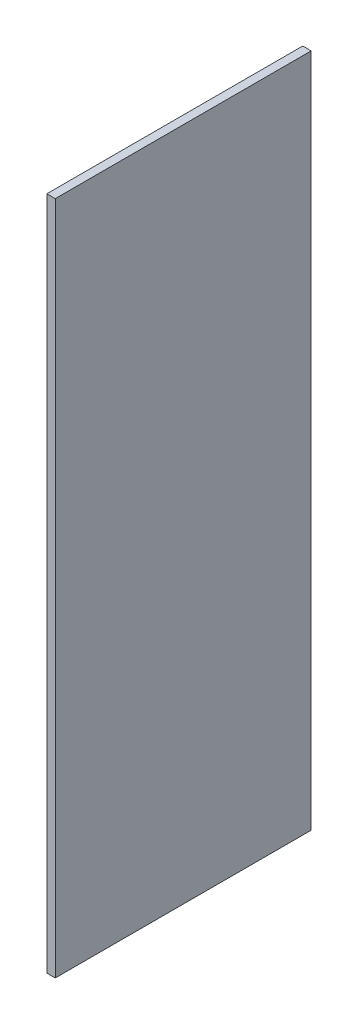
SolidWorks part; units mm, degrees
ref_plane "Front Plane" through (0, 0, 0) normal (0, 0, 1) x (1, 0, 0)
ref_plane "Top Plane" through (0, 0, 0) normal (0, 1, 0) x (1, 0, 0)
ref_plane "Right Plane" through (0, 0, 0) normal (1, 0, 0) x (0, 0, -1)
sketch "Sketch2" plane through (0, 0, 0) normal (1, 0, 0) x (0, 0, -1)
  line L1 (-1137.5, 3000) -> (1137.5, 3000)
  line L2 (-1137.5, 3000) -> (-1137.5, -3000)
  line L3 (-1137.5, -3000) -> (1137.5, -3000)
  line L4 (1137.5, 3000) -> (1137.5, -3000)
  line L5 (-1137.5, 3000) -> (1137.5, -3000) construction
  line L6 (-1137.5, -3000) -> (1137.5, 3000) construction
  point P0 (0, 0)
extrude "Boss-Extrude1" add sketch "Sketch2" along normal blind 75
